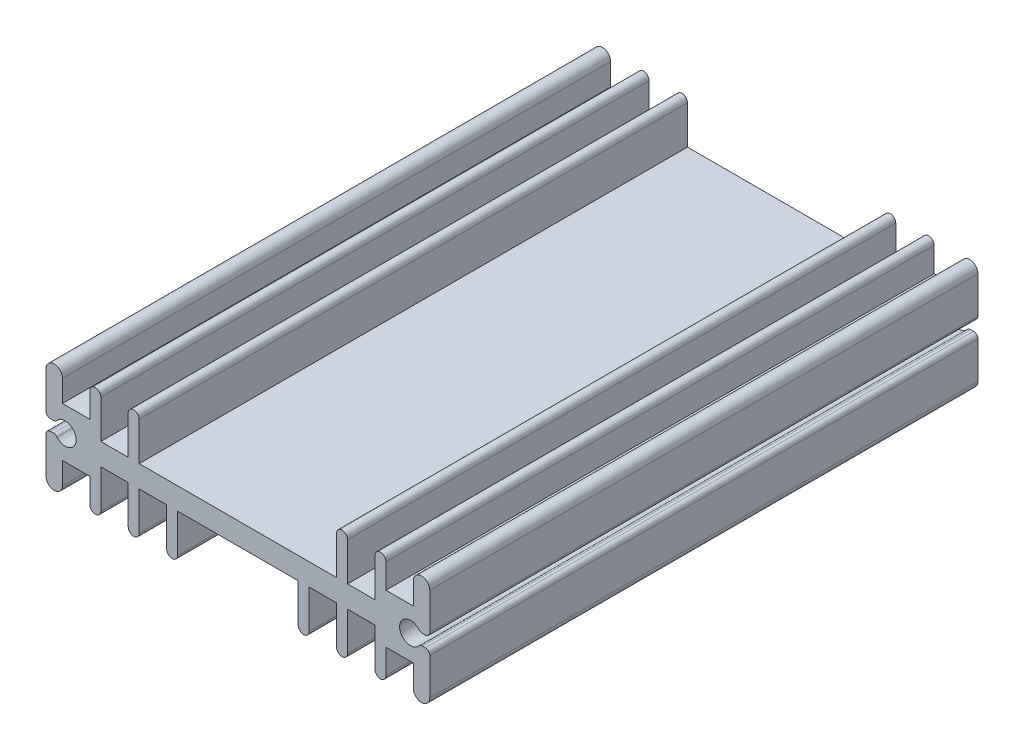
SolidWorks part; units mm, degrees
ref_plane "Front" through (0, 0, 0) normal (0, 0, 1) x (1, 0, 0)
ref_plane "Top" through (0, 0, 0) normal (0, 1, 0) x (1, 0, 0)
ref_plane "Right" through (0, 0, 0) normal (1, 0, 0) x (0, 0, -1)
sketch "Эскиз1" plane through (0, 0, 0) normal (0, 0, 1) x (1, 0, 0)
  line L1 (17.5, -4.25) -> (17.5, -0.5)
  line L10 (0, -1) -> (0, 1) construction
  line L11 (-17.5, -4.25) -> (-17.5, -0.5)
  line L18 (15.75, 0) -> (-15.75, 0) construction
  line L19 (-16.616, -0.5) -> (-17.5, -0.5)
  line L22 (16.616, -0.5) -> (17.5, -0.5)
  line L23 (5.5, -1) -> (5.5, -4.5)
  line L24 (16.616, 0.5) -> (17.5, 0.5)
  line L25 (17.5, 0.5) -> (17.5, 4.25)
  line L26 (-16.616, 0.5) -> (-17.5, 0.5)
  line L27 (-17.5, 0.5) -> (-17.5, 4.25)
  line L29 (-16, -4.25) -> (-16, -2.25)
  line L30 (-16, -2.25) -> (-13.5, -2.25)
  line L31 (-13.5, -2.25) -> (-13.5, -4.5)
  line L33 (-12.5, -4.5) -> (-12.5, -1)
  line L34 (-12.5, -1) -> (-10, -1)
  line L35 (-10, -1) -> (-10, -4.5)
  line L37 (-9, -4.5) -> (-9, -1)
  line L38 (-9, -1) -> (-6.5, -1)
  line L39 (-6.5, -1) -> (-6.5, -4.5)
  line L41 (-5.5, -4.5) -> (-5.5, -1)
  line L42 (-5.5, -1) -> (5.5, -1)
  line L43 (9, 1) -> (-9, 1)
  line L45 (6.5, -4.5) -> (6.5, -1)
  line L46 (6.5, -1) -> (9, -1)
  line L47 (9, -1) -> (9, -4.5)
  line L49 (10, -4.5) -> (10, -1)
  line L50 (10, -1) -> (12.5, -1)
  line L51 (12.5, -1) -> (12.5, -4.5)
  line L53 (13.5, -4.5) -> (13.5, -2.25)
  line L54 (13.5, -2.25) -> (16, -2.25)
  line L55 (16, -2.25) -> (16, -4.25)
  line L57 (9, 1) -> (9, 4.5)
  line L59 (10, 4.5) -> (10, 1)
  line L60 (10, 1) -> (12.5, 1)
  line L61 (12.5, 1) -> (12.5, 4.5)
  line L63 (13.5, 4.5) -> (13.5, 2.25)
  line L64 (13.5, 2.25) -> (16, 2.25)
  line L65 (16, 2.25) -> (16, 4.25)
  line L67 (-9, 1) -> (-9, 4.5)
  line L69 (-10, 4.5) -> (-10, 1)
  line L70 (-10, 1) -> (-12.5, 1)
  line L71 (-12.5, 1) -> (-12.5, 4.5)
  line L73 (-13.5, 4.5) -> (-13.5, 2.25)
  line L74 (-13.5, 2.25) -> (-16, 2.25)
  line L75 (-16, 2.25) -> (-16, 4.25)
  line L77 (17.5, -5) -> (-17.5, -5) construction
  line L78 (17.5, 5) -> (-17.5, 5) construction
  arc A1 (16.616, -0.5) -> (16.616, 0.5) centre (15.75, 0) cw
  arc A7 (-16.616, -0.5) -> (-16.616, 0.5) centre (-15.75, 0) ccw
  arc A8 (13.5, -4.5) -> (12.5, -4.5) centre (13, -4.5) cw
  arc A10 (10, -4.5) -> (9, -4.5) centre (9.5, -4.5) cw
  arc A12 (6.5, -4.5) -> (5.5, -4.5) centre (6, -4.5) cw
  arc A13 (16, -4.25) -> (17.5, -4.25) centre (16.75, -4.25) ccw
  arc A14 (-17.5, -4.25) -> (-16, -4.25) centre (-16.75, -4.25) ccw
  arc A15 (-13.5, -4.5) -> (-12.5, -4.5) centre (-13, -4.5) ccw
  arc A16 (-10, -4.5) -> (-9, -4.5) centre (-9.5, -4.5) ccw
  arc A17 (-6.5, -4.5) -> (-5.5, -4.5) centre (-6, -4.5) ccw
  arc A18 (-9, 4.5) -> (-10, 4.5) centre (-9.5, 4.5) ccw
  arc A19 (-12.5, 4.5) -> (-13.5, 4.5) centre (-13, 4.5) ccw
  arc A20 (-16, 4.25) -> (-17.5, 4.25) centre (-16.75, 4.25) ccw
  arc A21 (16, 4.25) -> (17.5, 4.25) centre (16.75, 4.25) cw
  arc A22 (13.5, 4.5) -> (12.5, 4.5) centre (13, 4.5) ccw
  arc A23 (10, 4.5) -> (9, 4.5) centre (9.5, 4.5) ccw
  dimension "D1" = 35
  dimension "D6" = 2
  dimension "D10" = 4.5
  dimension "D11" = 1
  dimension "D2" = 1
  dimension "D3" = 31.5
  dimension "D4" = 10
  dimension "D5" = 11
  dimension "D7" = 2.5
  dimension "D8" = 1
  dimension "D9" = 18
extrude "Бобышка-Вытянуть1" add sketch "Эскиз1" along normal blind 50
fillet "Скругление1" radius 0.4 8 edges at (-16.616, -0.5, 25) (-17.5, -0.5, 25) (-17.5, 0.5, 25) (-16.616, 0.5, 25) (17.5, 0.5, 25) (16.616, 0.5, 25) (17.5, -0.5, 25) (16.616, -0.5, 25)
